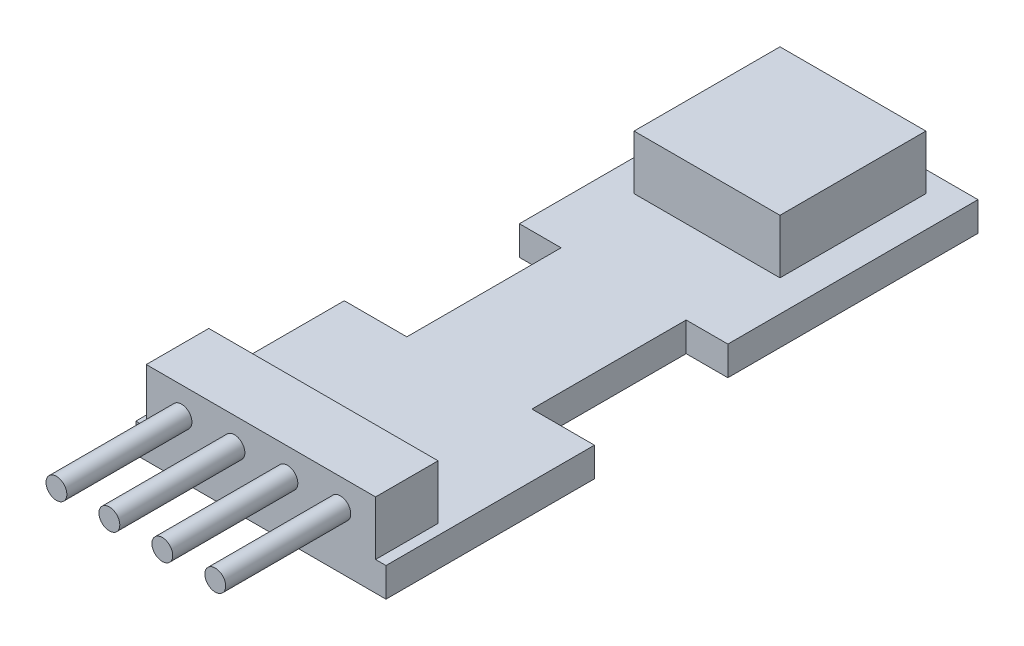
SolidWorks part; units mm, degrees
ref_plane "Front Plane" through (0, 0, 0) normal (0, 0, 1) x (1, 0, 0)
ref_plane "Top Plane" through (0, 0, 0) normal (0, 1, 0) x (1, 0, 0)
ref_plane "Right Plane" through (0, 0, 0) normal (1, 0, 0) x (0, 0, -1)
sketch "Sketch1" plane through (0, 0, 0) normal (0, 1, 0) x (1, 0, 0)
  line L0 (0, 0) -> (0, 5)
  line L1 (0, 5) -> (1.5, 5)
  line L2 (1.5, 5) -> (1.5, 8.7)
  line L3 (1.5, 8.7) -> (0.5, 8.7)
  line L4 (0.5, 8.7) -> (0.5, 14.7)
  line L5 (0.5, 14.7) -> (5.5, 14.7)
  line L6 (0, 0) -> (6, 0)
  line L7 (3, 14.7) -> (3, 0) construction
  line L8 (6, 0) -> (6, 5)
  line L9 (6, 5) -> (4.5, 5)
  line L10 (4.5, 5) -> (4.5, 8.7)
  line L11 (4.5, 8.7) -> (5.5, 8.7)
  line L12 (5.5, 8.7) -> (5.5, 14.7)
  point P15 (4.5, 6.85)
  dimension "D1" = 5
  dimension "D2" = 6
  dimension "D3" = 3
  dimension "D4" = 6
  dimension "D5" = 14.7
  dimension "D6" = 5
extrude "Boss-Extrude1" add sketch "Sketch1" along normal blind 0.7
sketch "Sketch2" plane through (0, 0.7, 0) normal (0, 1, 0) x (1, 0, 0)
  line L0 (5.5, 14.7) -> (0.5, 14.7) construction
  line L1 (1.25, 14.2) -> (4.75, 14.2)
  line L2 (1.25, 14.2) -> (1.25, 10.7)
  line L3 (1.25, 10.7) -> (4.75, 10.7)
  line L4 (4.75, 14.2) -> (4.75, 10.7)
  line L5 (0, 0) -> (6, 0) construction
  line L6 (0.25, 0) -> (5.75, 0)
  line L7 (0.25, 0) -> (0.25, 1.5)
  line L8 (0.25, 1.5) -> (5.75, 1.5)
  line L9 (5.75, 0) -> (5.75, 1.5)
  point P6 (3, 14.2)
  point P7 (3, 14.7)
  point P14 (3, 1.5)
  point P15 (3, 10.7)
  dimension "D1" = 3.5
  dimension "D2" = 5.5
  dimension "D3" = 0.5
  dimension "D4" = 1.5
extrude "Boss-Extrude2" add sketch "Sketch2" along normal blind 1.3
sketch "Sketch3" plane through (0, 0, 0) normal (0, 0, 1) x (1, 0, 0)
  line L0 (1.095, 1.35) -> (4.905, 1.35) construction
  line L1 (0.25, 2) -> (5.75, 2) construction
  line L2 (0.25, 2) -> (0.25, 0.7) construction
  circle A0 centre (1.095, 1.35) radius 0.25
  circle A1 centre (2.365, 1.35) radius 0.25
  circle A2 centre (3.635, 1.35) radius 0.25
  circle A3 centre (4.905, 1.35) radius 0.25
  point P2 (3, 1.35)
  point P5 (3, 2)
  point P8 (0.25, 1.35)
  dimension "D4" = 0.5
  dimension "D1" = 1.27
  dimension "D2" = 1.27
  dimension "D3" = 1.27
extrude "Boss-Extrude3" add sketch "Sketch3" along normal blind 3
equation "\"D2@Sketch3\"=\"D1@Sketch3\""
equation "\"D3@Sketch3\"=\"D1@Sketch3\""
